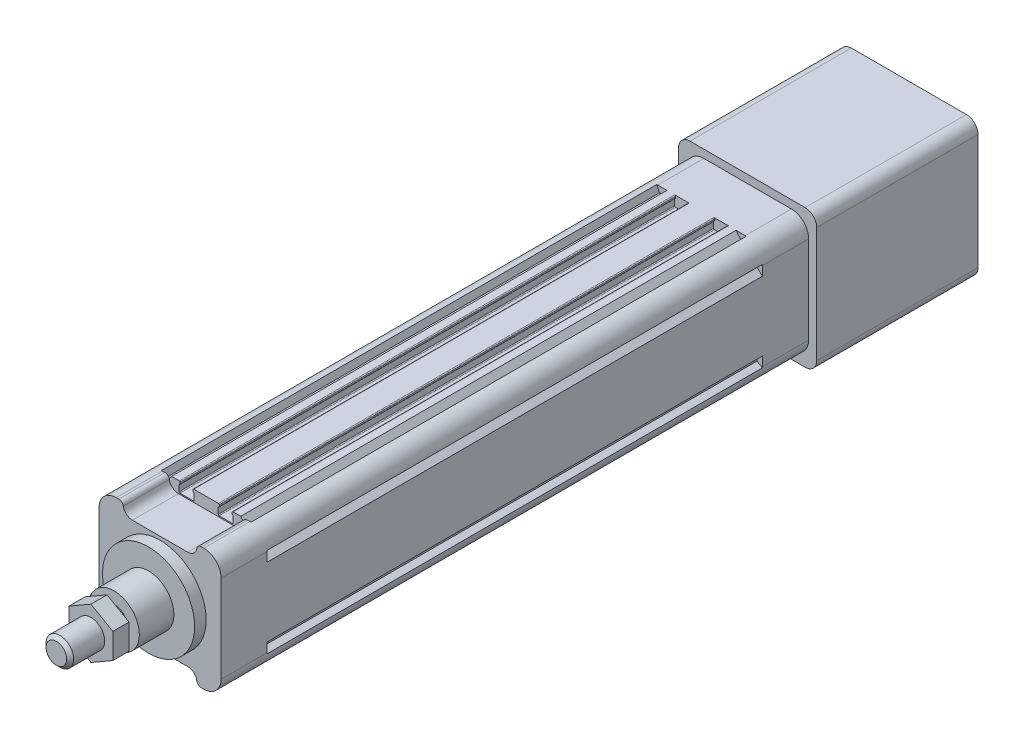
SolidWorks part; units mm, degrees
ref_plane "Front" through (0, 0, 0) normal (0, 0, 1) x (1, 0, 0)
ref_plane "Top" through (0, 0, 0) normal (0, 1, 0) x (1, 0, 0)
ref_plane "Right" through (0, 0, 0) normal (1, 0, 0) x (0, 0, -1)
sketch "草图1" plane through (0, 0, 0) normal (0, 0, 1) x (1, 0, 0)
  line L0 (19.7737, 3) -> (23.3, 3)
  line L1 (23.3, 3) -> (23.3, -3)
  line L2 (23.3, -3) -> (19.7737, -3)
  line L3 (-19.7737, -3) -> (-23.3, -3)
  line L4 (-23.3, -3) -> (-23.3, 3)
  line L5 (-23.3, 3) -> (-19.7737, 3)
  line L6 (-18.2, 24) -> (-19.4434, 26.4869)
  line L7 (-26.4869, 19.4434) -> (-24, 18.2)
  line L8 (-24, 18.2) -> (-24, 17.1)
  line L9 (-24, 17.1) -> (-26.5, 15)
  line L10 (-26.5, 15) -> (-26.5, -15)
  line L11 (-26.5, -15) -> (-24, -17.1)
  line L12 (-24, -17.1) -> (-24, -18.2)
  line L13 (-24, -18.2) -> (-26.4869, -19.4434)
  line L14 (-19.4434, -26.4869) -> (-18.2, -24)
  line L15 (-18.2, -24) -> (-17.1, -24)
  line L16 (-17.1, -24) -> (-15, -26.5)
  line L17 (-15, -26.5) -> (-11.65, -26.5)
  line L18 (-11.25, -26.1) -> (-11.25, -25.6)
  line L19 (-11.65, -25.2) -> (-11.75, -25.2)
  line L20 (-11.75, -25.2) -> (-11.75, -22.4)
  line L21 (-11.35, -22) -> (-5.65, -22)
  line L22 (-5.25, -22.4) -> (-5.25, -25.2)
  line L23 (-5.25, -25.2) -> (-5.35, -25.2)
  line L24 (-5.75, -25.6) -> (-5.75, -26.1)
  line L25 (-5.35, -26.5) -> (5.35, -26.5)
  line L26 (5.75, -26.1) -> (5.75, -25.6)
  line L27 (5.35, -25.2) -> (5.25, -25.2)
  line L28 (5.25, -25.2) -> (5.25, -22.4)
  line L29 (5.65, -22) -> (11.35, -22)
  line L30 (11.75, -22.4) -> (11.75, -25.2)
  line L31 (11.75, -25.2) -> (11.65, -25.2)
  line L32 (11.25, -25.6) -> (11.25, -26.1)
  line L33 (11.65, -26.5) -> (15, -26.5)
  line L34 (15, -26.5) -> (17.1, -24)
  line L35 (17.1, -24) -> (18.2, -24)
  line L36 (18.2, -24) -> (19.4434, -26.4869)
  line L37 (26.4869, -19.4434) -> (24, -18.2)
  line L38 (24, -18.2) -> (24, -17.1)
  line L39 (24, -17.1) -> (26.5, -15)
  line L40 (26.5, -15) -> (26.5, 15)
  line L41 (26.5, 15) -> (24, 17.1)
  line L42 (24, 17.1) -> (24, 18.2)
  line L43 (24, 18.2) -> (26.4869, 19.4434)
  line L44 (19.4434, 26.4869) -> (18.2, 24)
  line L45 (18.2, 24) -> (17.1, 24)
  line L46 (17.1, 24) -> (15, 26.5)
  line L47 (15, 26.5) -> (11.65, 26.5)
  line L48 (11.25, 26.1) -> (11.25, 25.6)
  line L49 (11.65, 25.2) -> (11.75, 25.2)
  line L50 (11.75, 25.2) -> (11.75, 22.4)
  line L51 (11.35, 22) -> (5.65, 22)
  line L52 (5.25, 22.4) -> (5.25, 25.2)
  line L53 (5.25, 25.2) -> (5.35, 25.2)
  line L54 (5.75, 25.6) -> (5.75, 26.1)
  line L55 (5.35, 26.5) -> (-5.35, 26.5)
  line L56 (-5.75, 26.1) -> (-5.75, 25.6)
  line L57 (-5.35, 25.2) -> (-5.25, 25.2)
  line L58 (-5.25, 25.2) -> (-5.25, 22.4)
  line L59 (-5.65, 22) -> (-11.35, 22)
  line L60 (-11.75, 22.4) -> (-11.75, 25.2)
  line L61 (-11.75, 25.2) -> (-11.65, 25.2)
  line L62 (-11.25, 25.6) -> (-11.25, 26.1)
  line L63 (-11.65, 26.5) -> (-15, 26.5)
  line L64 (-15, 26.5) -> (-17.1, 24)
  line L65 (-17.1, 24) -> (-18.2, 24)
  arc A0 (19.7737, 3) -> (-19.7737, 3) centre (0, 0) ccw
  arc A1 (-19.7737, -3) -> (19.7737, -3) centre (0, 0) ccw
  circle A2 centre (19, 19) radius 2.1
  circle A3 centre (19, -19) radius 2.1
  circle A4 centre (-19, -19) radius 2.1
  circle A5 centre (-19, 19) radius 2.1
  arc A6 (-19.4434, 26.4869) -> (-26.4869, 19.4434) centre (-19, 19) ccw
  arc A7 (-26.4869, -19.4434) -> (-19.4434, -26.4869) centre (-19, -19) ccw
  arc A8 (-11.65, -26.5) -> (-11.25, -26.1) centre (-11.65, -26.1) ccw
  arc A9 (-11.25, -25.6) -> (-11.65, -25.2) centre (-11.65, -25.6) ccw
  arc A10 (-11.35, -22) -> (-11.75, -22.4) centre (-11.35, -22.4) ccw
  arc A11 (-5.25, -22.4) -> (-5.65, -22) centre (-5.65, -22.4) ccw
  arc A12 (-5.35, -25.2) -> (-5.75, -25.6) centre (-5.35, -25.6) ccw
  arc A13 (-5.75, -26.1) -> (-5.35, -26.5) centre (-5.35, -26.1) ccw
  arc A14 (5.35, -26.5) -> (5.75, -26.1) centre (5.35, -26.1) ccw
  arc A15 (5.75, -25.6) -> (5.35, -25.2) centre (5.35, -25.6) ccw
  arc A16 (5.65, -22) -> (5.25, -22.4) centre (5.65, -22.4) ccw
  arc A17 (11.75, -22.4) -> (11.35, -22) centre (11.35, -22.4) ccw
  arc A18 (11.65, -25.2) -> (11.25, -25.6) centre (11.65, -25.6) ccw
  arc A19 (11.25, -26.1) -> (11.65, -26.5) centre (11.65, -26.1) ccw
  arc A20 (19.4434, -26.4869) -> (26.4869, -19.4434) centre (19, -19) ccw
  arc A21 (26.4869, 19.4434) -> (19.4434, 26.4869) centre (19, 19) ccw
  arc A22 (11.65, 26.5) -> (11.25, 26.1) centre (11.65, 26.1) ccw
  arc A23 (11.25, 25.6) -> (11.65, 25.2) centre (11.65, 25.6) ccw
  arc A24 (11.35, 22) -> (11.75, 22.4) centre (11.35, 22.4) ccw
  arc A25 (5.25, 22.4) -> (5.65, 22) centre (5.65, 22.4) ccw
  arc A26 (5.35, 25.2) -> (5.75, 25.6) centre (5.35, 25.6) ccw
  arc A27 (5.75, 26.1) -> (5.35, 26.5) centre (5.35, 26.1) ccw
  arc A28 (-5.35, 26.5) -> (-5.75, 26.1) centre (-5.35, 26.1) ccw
  arc A29 (-5.75, 25.6) -> (-5.35, 25.2) centre (-5.35, 25.6) ccw
  arc A30 (-5.65, 22) -> (-5.25, 22.4) centre (-5.65, 22.4) ccw
  arc A31 (-11.75, 22.4) -> (-11.35, 22) centre (-11.35, 22.4) ccw
  arc A32 (-11.65, 25.2) -> (-11.25, 25.6) centre (-11.65, 25.6) ccw
  arc A33 (-11.25, 26.1) -> (-11.65, 26.5) centre (-11.65, 26.1) ccw
extrude "凸台-拉伸1" add sketch "草图1" along normal blind 215
sketch "草图6" plane through (0, 0, 215) normal (0, 0, 1) x (1, 0, 0)
  line L0 (0, 0) -> (19, 0) construction
  line L2 (-26.5, -19) -> (-26.5, 19)
  line L3 (-19, 26.5) -> (-17.9161, 26.5)
  line L4 (26.5, -19) -> (26.5, 19)
  line L5 (-26.5, -26.5) -> (26.5, 26.5) construction
  line L6 (-26.5, 26.5) -> (26.5, -26.5) construction
  line L7 (-12, 21.5) -> (12, 21.5)
  line L9 (19, 26.5) -> (17.9161, 26.5)
  line L10 (19, -26.5) -> (17.9161, -26.5)
  line L11 (-12, -21.5) -> (12, -21.5)
  line L12 (-19, -26.5) -> (-17.9161, -26.5)
  arc A0 (12, 21.5) -> (15.9441, 24.8333) centre (12, 25.5) ccw
  arc A1 (-15.9441, 24.8333) -> (-12, 21.5) centre (-12, 25.5) ccw
  arc A2 (-15.9441, 24.8333) -> (-17.9161, 26.5) centre (-17.9161, 24.5) ccw
  arc A3 (15.9441, 24.8333) -> (17.9161, 26.5) centre (17.9161, 24.5) cw
  arc A4 (-26.5, -19) -> (-19, -26.5) centre (-19, -19) ccw
  arc A5 (19, -26.5) -> (26.5, -19) centre (19, -19) ccw
  arc A6 (26.5, 19) -> (19, 26.5) centre (19, 19) ccw
  arc A7 (-26.5, 19) -> (-19, 26.5) centre (-19, 19) cw
  arc A8 (15.9441, -24.8333) -> (17.9161, -26.5) centre (17.9161, -24.5) ccw
  arc A9 (12, -21.5) -> (15.9441, -24.8333) centre (12, -25.5) cw
  arc A10 (-15.9441, -24.8333) -> (-12, -21.5) centre (-12, -25.5) cw
  arc A11 (-15.9441, -24.8333) -> (-17.9161, -26.5) centre (-17.9161, -24.5) cw
  point P0 (0, 0)
  point P9 (0, 21.5)
  point P13 (20, 20.8461)
  point P16 (-12, 20.8461)
  dimension "D5" = 4
  dimension "D6" = 2
  dimension "D7" = 2
  dimension "D9" = 7.5
  dimension "D1" = 53
  dimension "D2" = 53
  dimension "D3" = 26.5
  dimension "D4" = 24
  dimension "D8" = 5
extrude "凸台-拉伸2" add sketch "草图6" along normal blind 20
sketch "草图7" plane through (0, 0, 235) normal (0, 0, 1) x (1, 0, 0)
  circle A0 centre (0, 0) radius 20
  dimension "D1" = 40
extrude "凸台-拉伸3" add sketch "草图7" along normal blind 5
sketch "草图9" plane through (0, 0, 240) normal (0, 0, 1) x (1, 0, 0)
  circle A0 centre (0, 0) radius 11
  dimension "D1" = 22
extrude "凸台-拉伸4" add sketch "草图9" along normal blind 15
sketch "草图10" plane through (0, 0, 255) normal (0, 0, 1) x (1, 0, 0)
  circle A0 centre (0, 0) radius 6
  dimension "D1" = 12
extrude "凸台-拉伸5" add sketch "草图10" along normal blind 25
sketch "草图11" plane through (0, 0, 0) normal (0, 0, -1) x (-1, 0, 0)
  line L1 (-19, -26.5) -> (19, -26.5)
  line L2 (-26.5, -19) -> (-26.5, 19)
  line L3 (-19, 26.5) -> (19, 26.5)
  line L4 (26.5, -19) -> (26.5, 19)
  line L5 (-26.5, -26.5) -> (26.5, 26.5) construction
  line L6 (-26.5, 26.5) -> (26.5, -26.5) construction
  arc A0 (-26.5, -19) -> (-19, -26.5) centre (-19, -19) ccw
  arc A1 (19, -26.5) -> (26.5, -19) centre (19, -19) ccw
  arc A2 (26.5, 19) -> (19, 26.5) centre (19, 19) ccw
  arc A3 (-26.5, 19) -> (-19, 26.5) centre (-19, 19) cw
  point P0 (0, 0)
  dimension "D3" = 7.5
  dimension "D1" = 53
  dimension "D2" = 53
extrude "凸台-拉伸6" add sketch "草图11" along normal blind 20
sketch "草图12" plane through (0, 0, -20) normal (0, 0, -1) x (-1, 0, 0)
  line L1 (-25, -30) -> (25, -30)
  line L2 (-30, -25) -> (-30, 25)
  line L3 (-25, 30) -> (25, 30)
  line L4 (30, -25) -> (30, 25)
  line L5 (-30, -30) -> (30, 30) construction
  line L6 (-30, 30) -> (30, -30) construction
  arc A0 (-30, -25) -> (-25, -30) centre (-25, -25) ccw
  arc A1 (25, -30) -> (30, -25) centre (25, -25) ccw
  arc A2 (30, 25) -> (25, 30) centre (25, 25) ccw
  arc A3 (-30, 25) -> (-25, 30) centre (-25, 25) cw
  point P0 (0, 0)
  dimension "D3" = 5
  dimension "D1" = 60
  dimension "D2" = 60
extrude "凸台-拉伸7" add sketch "草图12" along normal blind 70
sketch "草图14" plane through (0, 0, -90) normal (0, 0, -1) x (-1, 0, 0)
  circle A0 centre (0, 0) radius 19
  dimension "D1" = 38
extrude "切除-拉伸2" cut sketch "草图14" against normal blind 70
hole_wizard "M6 螺纹孔1" positions "草图15" profile "草图16" tap size "M6" standard "GB"
sketch "草图15" plane through (-26.5, 0, 0) normal (-1, 0, 0) x (0, 0, 1)
  line L0 (-20, -25) -> (-20, 25) construction
  line L1 (235, 19) -> (235, -19) construction
  point P0 (225, 11)
  point P2 (225, -11)
  point P4 (-10, 11)
  point P6 (-10, -11)
  dimension "D1" = 10
  dimension "D2" = 10
  dimension "D3" = 11
  dimension "D4" = 11
  dimension "D5" = 10
  dimension "D6" = 10
  dimension "D7" = 22
  dimension "D8" = 11
sketch "草图16" plane through (-26.5, 11, 225) normal (0, 1, 0) x (0, 0, 1)
  line L0 (0, 0) -> (0, 16.5022)
  line L1 (0, 16.5022) -> (2.5, 15)
  line L2 (2.5, 15) -> (2.5, 0)
  line L5 (2.5, 0) -> (0, 0)
  line L10 (0, 16.5022) -> (-2.5, 15) construction
  line L11 (0, -6.35) -> (0, 107.95) construction
  dimension "螺纹孔钻头直径" = 5
  dimension "螺纹孔钻头深度" = 15
  dimension "导头角度" = 118
cosmetic thread "孔螺蚊线4" parameters "D1"=12, "D2"=6
cosmetic thread "孔螺蚊线5" parameters "D1"=12, "D2"=6
cosmetic thread "孔螺蚊线6" parameters "D1"=12, "D2"=6
cosmetic thread "孔螺蚊线7" parameters "D1"=12, "D2"=6
chamfer "倒角1" distance 1.5 angle 45 1 edges at (6, 0, 280)
sketch "草图17" plane through (0, 0, 255) normal (0, 0, 1) x (1, 0, 0)
  line L1 (0, 10.9697) -> (-9.5, 5.4848)
  line L2 (-9.5, 5.4848) -> (-9.5, -5.4848)
  line L3 (-9.5, -5.4848) -> (0, -10.9697)
  line L4 (0, -10.9697) -> (9.5, -5.4848)
  line L5 (9.5, -5.4848) -> (9.5, 5.4848)
  line L6 (9.5, 5.4848) -> (0, 10.9697)
  circle A0 centre (0, 0) radius 9.5 construction
  dimension "D1" = 19
extrude "凸台-拉伸8" add sketch "草图17" along normal blind 7 from offset 3
